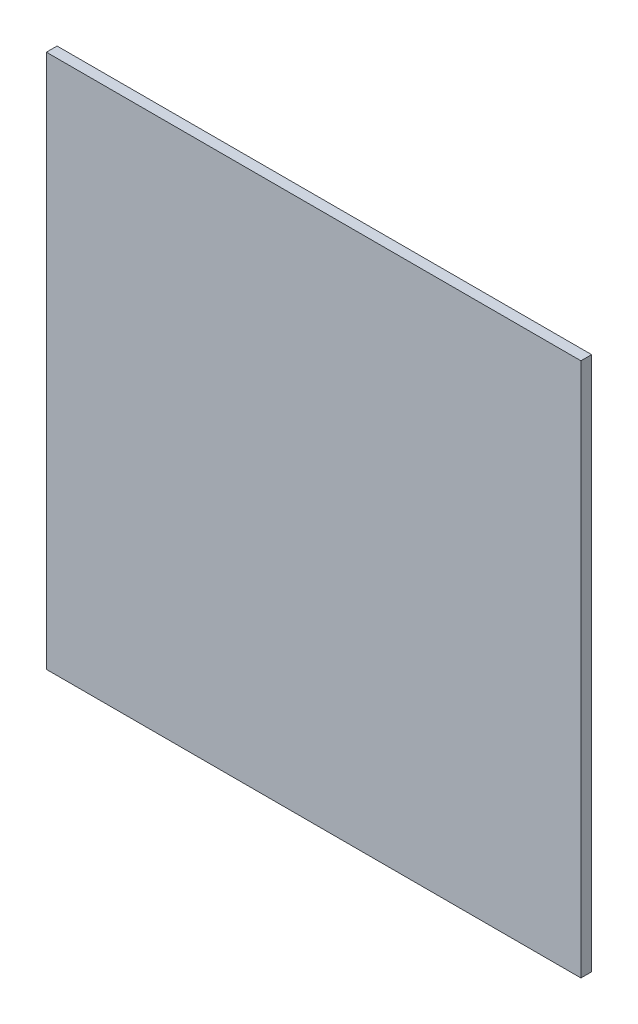
SolidWorks part; units mm, degrees
ref_plane "前视基准面" through (0, 0, 0) normal (0, 0, 1) x (1, 0, 0)
ref_plane "上视基准面" through (0, 0, 0) normal (0, 1, 0) x (1, 0, 0)
ref_plane "右视基准面" through (0, 0, 0) normal (1, 0, 0) x (0, 0, -1)
sketch "草图1" plane through (0, 0, 0) normal (0, 0, 1) x (1, 0, 0)
  line L1 (-52.7806, 43.3353) -> (47.2194, 43.3353)
  line L2 (-52.7806, 43.3353) -> (-52.7806, -56.6647)
  line L3 (-52.7806, -56.6647) -> (47.2194, -56.6647)
  line L4 (47.2194, 43.3353) -> (47.2194, -56.6647)
extrude "凸台-拉伸2" add sketch "草图1" along normal blind 2
